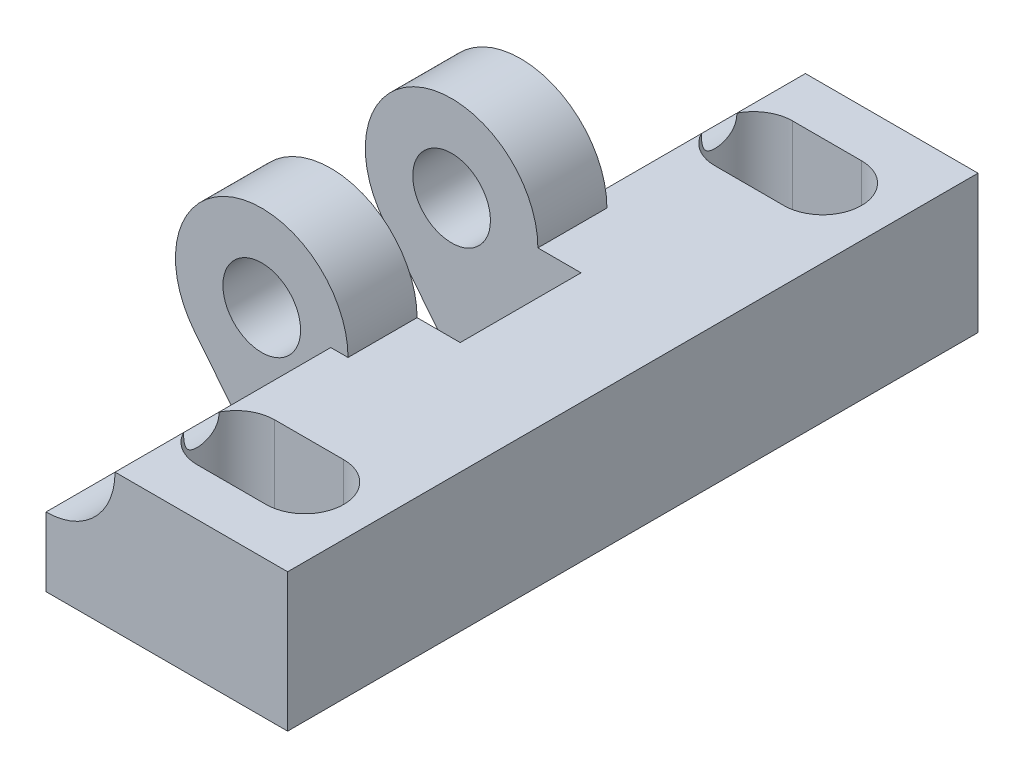
SolidWorks part; units mm, degrees
material "Printed PLA"
ref_plane "Front Plane" through (0, 0, 0) normal (0, 0, 1) x (1, 0, 0)
ref_plane "Top Plane" through (0, 0, 0) normal (0, 1, 0) x (1, 0, 0)
ref_plane "Right Plane" through (0, 0, 0) normal (1, 0, 0) x (0, 0, -1)
sketch "Sketch1" plane through (0, 0, 0) normal (0, 1, 0) x (1, 0, 0)
  line L1 (0, 7.5) -> (-13, 7.5)
  line L2 (0, 7.5) -> (0, -7.5)
  line L3 (0, -7.5) -> (-13, -7.5)
  line L4 (-13, 7.5) -> (-13, -7.5)
  dimension "D1" = 15
  dimension "D2" = 13
extrude "Boss-Extrude1" add sketch "Sketch1" along normal blind 8
sketch "Sketch2" plane through (0, 0, 7.5) normal (0, 0, 1) x (1, 0, 0)
  line L0 (-13, 0) -> (0, 0) construction
  line L1 (0, 8) -> (0, 0) construction
  line L2 (-16.9031, 4.875) -> (-13, 0)
  line L3 (-13, 0) -> (-13, 3)
  line L4 (-13, 8) -> (-13, 0) construction
  arc A0 (-13, 3) -> (-16.9031, 4.875) centre (-13, 8) ccw
  dimension "D1" = 10
  dimension "D3" = 13
  dimension "D2" = 8
extrude "Boss-Extrude2" add sketch "Sketch2" against normal offset from surface (4 mm away) 3.5 up to plane "Front Plane"
mirror "Mirror1" about plane through (0, 0, 0) normal (0, 0, 1) of "Boss-Extrude2"
sketch "Sketch6" plane through (0, 0, 0) normal (0, -1, 0) x (1, 0, 0)
  line L1 (1, 20) -> (-13, 20)
  line L2 (1, 20) -> (1, -20)
  line L3 (1, -20) -> (-13, -20)
  line L4 (-13, 20) -> (-13, -20)
  line L6 (-7, 15) -> (-3, 15) construction
  line L7 (-7, 17.25) -> (-3, 17.25)
  line L8 (-7, 12.75) -> (-3, 12.75)
  line L9 (-7, -15) -> (-3, -15) construction
  line L10 (-7, -12.75) -> (-3, -12.75)
  line L11 (-7, -17.25) -> (-3, -17.25)
  line L12 (-5, -15) -> (-5, 15) construction
  line L13 (-5, 0) -> (0, 0) construction
  line L14 (-5, 0) -> (-13, 0) construction
  line L15 (0, 7.5) -> (0, -7.5) construction
  arc A0 (-7, 17.25) -> (-7, 12.75) centre (-7, 15) ccw
  arc A1 (-3, 12.75) -> (-3, 17.25) centre (-3, 15) ccw
  arc A2 (-7, -12.75) -> (-7, -17.25) centre (-7, -15) ccw
  arc A3 (-3, -17.25) -> (-3, -12.75) centre (-3, -15) ccw
  point P10 (-5, 15)
  point P15 (-5, -15)
  dimension "D1" = 6
  dimension "D2" = 4
  dimension "D3" = 4.5
  dimension "D4" = 30
  dimension "D5" = 40
  dimension "D6" = 1
  dimension "D7" = 14
extrude "Boss-Extrude3" add sketch "Sketch6" against normal blind 8
sketch "Sketch3" plane through (0, 0, -3.5) normal (0, 0, 1) x (1, 0, 0)
  circle A0 centre (-13, 8) radius 7.5
  dimension "D1" = 15
extrude "Cut-Extrude1" cut sketch "Sketch3" along normal up to surface (7 mm away) up to face at (-13.2769, 6.7888, 3.5)
sketch "Sketch4" plane through (0, 0, 7.5) normal (0, 0, 1) x (1, 0, 0)
  circle A0 centre (-13, 8) radius 2.25
  dimension "D1" = 4.5
extrude "Cut-Extrude2" cut sketch "Sketch4" against normal through all and the other way through all
sketch "Sketch7" plane through (0, 0, 7.5) normal (0, 0, 1) x (1, 0, 0)
  circle A0 centre (-13, 8) radius 4
  dimension "D1" = 8
extrude "Cut-Extrude3" cut sketch "Sketch7" along normal through all
mirror "Mirror2" about plane through (0, 0, 0) normal (0, 0, 1) of "Cut-Extrude3"
